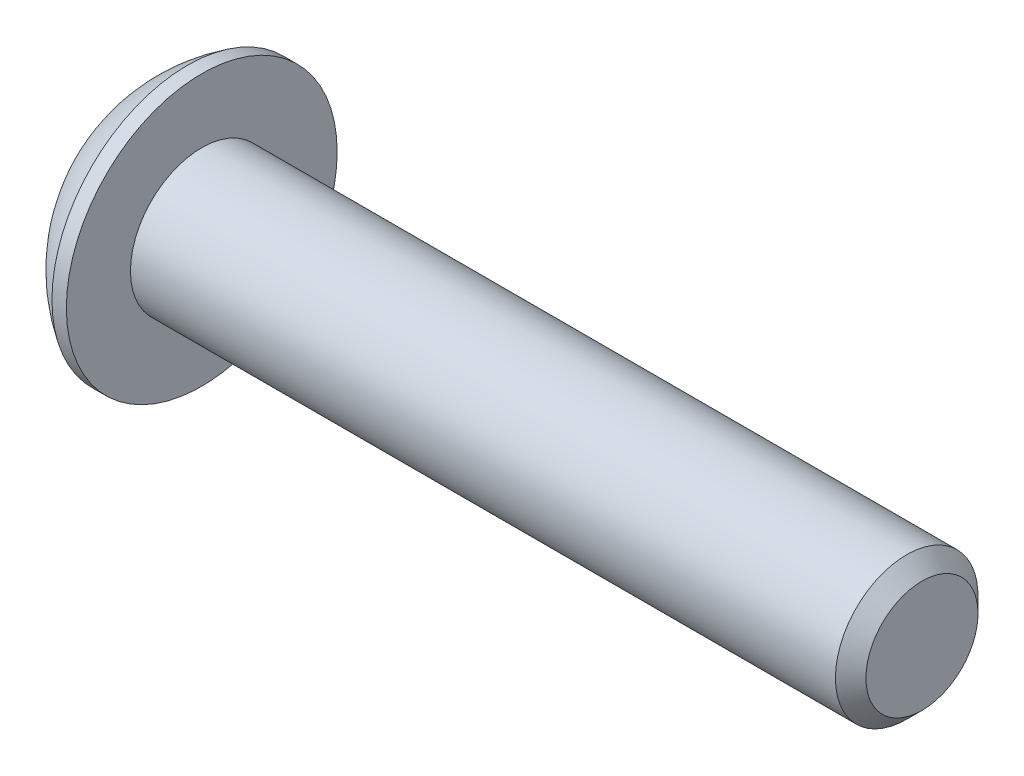
SolidWorks part; units mm, degrees
ref_plane "Plane1" through (0, 0, 0) normal (0, 0, 1) x (1, 0, 0)
ref_plane "Plane2" through (0, 0, 0) normal (0, 1, 0) x (1, 0, 0)
ref_plane "Plane3" through (0, 0, 0) normal (1, 0, 0) x (0, 0, -1)
sketch "BodySke" plane through (0, 0, 0) normal (0, 0, 1) x (1, 0, 0)
  line L0 (14.0208, 0) -> (14.0208, 0.9881)
  line L1 (13.7516, 1.2573) -> (1.3208, 1.2573)
  line L2 (1.3208, 1.2573) -> (1.3208, 2.3876)
  line L3 (1.3208, 2.3876) -> (1.0668, 2.3876)
  line L4 (0, 0) -> (101.6, 0) construction
  line L5 (1.3208, -2.3876) -> (1.0668, -2.3876) construction
  line L6 (55.6768, -1.2573) -> (1.3208, -1.2573) construction
  line L7 (14.0208, 0) -> (0, 0)
  line L8 (0, 1.1938) -> (0, -1.1938) construction
  line L9 (0, 0) -> (0, 1.1938)
  line L10 (14.0208, 0.9881) -> (13.7516, 1.2573)
  line L11 (14.0208, -0.9881) -> (13.7516, -1.2573) construction
  line L12 (1.7755, 9.525) -> (1.7755, -1.2573) construction
  line L13 (1.3208, 9.525) -> (1.3208, -1.2573) construction
  arc A1 (0, 1.1938) -> (1.0668, 2.3876) centre (2.5373, 0) cw
  dimension "D1" = 2.3876
  dimension "Diameter" = 2.5146
  dimension "Length" = 12.7
  dimension "Head_dia" = 4.7752
  dimension "Head_ht" = 1.3208
  dimension "Head_side_ht" = 0.254
  dimension "Minor_dia" = 1.9761
  dimension "Body_ch_ang" = 45
  dimension "Advance" = 0.4547
  dimension "Thread_nom" = 12.7
revolve "BaseBody" add sketch "BodySke" angle 360 about L4
cosmetic thread "ThreadCosmetic" parameters "Thread_length"=12.2453, "Thread_minor"=1.9761
sketch "Sketch2" plane through (0, 0, 0) normal (0, 0, 1) x (1, 0, 0)
  line L0 (0, 0.7874) -> (0.889, 0.7874)
  line L1 (0.889, 0.7874) -> (1.3436, 0)
  line L3 (1.3436, 0) -> (0, 0)
  line L4 (0, 0) -> (0, 0.7874)
  line L5 (0, -0.7874) -> (0.889, -0.7874) construction
  line L6 (0, 0) -> (47.625, 0) construction
  dimension "D2" = 60
  dimension "PreBroach_depth" = 0.889
  dimension "PreBroach_dia" = 1.5748
revolve "PreBroach" cut sketch "Sketch2" angle 360 about L6
sketch "Sketch3" plane through (0, 0, 0) normal (1, 0, 0) x (0, 0, -1)
  line L0 (-0.7874, -0.4546) -> (-0.7874, 0.4546)
  line L1 (-0.7874, 0.4546) -> (0, 0.9092)
  line L2 (0, 0.9092) -> (0.7874, 0.4546)
  line L3 (0.7874, 0.4546) -> (0.7874, -0.4546)
  line L4 (0.7874, -0.4546) -> (0, -0.9092)
  line L5 (0, -0.9092) -> (-0.7874, -0.4546)
  dimension "D1" = 0.7874
  dimension "D2" = 0.7874
  dimension "D3" = 1.5748
  dimension "Hex_size" = 1.5748
extrude "Hex" cut sketch "Sketch3" along normal blind 0.889
sketch "Sketch4" plane through (0, 9.525, 0) normal (1, 0, 0) x (0, 0, -1)
  line L0 (0, -9.525) -> (0.9398, -9.525)
  line L1 (0, -9.525) -> (6.1484, -5.9752) construction
  line L2 (0, -9.525) -> (0.4699, -8.7111)
  line L3 (0.7832, -9.3075) -> (0.8962, -9.2422)
  line L4 (0.58, -8.9555) -> (0.693, -8.8902)
  arc A0 (0.7832, -9.3075) -> (0.58, -8.9555) centre (0, -9.525) ccw
  arc A1 (0.9398, -9.525) -> (0.8962, -9.2422) centre (0, -9.525) ccw
  arc A2 (0.4699, -8.7111) -> (0.693, -8.8902) centre (0, -9.525) cw
  dimension "D1" = 30
  dimension "Spline_n_dim" = 1.6256
  dimension "Spline_m_dim" = 1.8796
  dimension "D2" = 60
  dimension "D3" = 0.2032
  dimension "Spline_p_dim" = 0.4064
extrude "Spline" [suppressed] cut sketch "Sketch4" along normal blind 0.889
pattern_circular "CirPattern1" [suppressed] count 6 every 60 about axis through (0, 0, 0) along (1, 0, 0)
sketch "ThdSchSke" plane through (0, 0, 0) normal (0, 0, 1) x (1, 0, 0)
  line L0 (1.7755, -0.9881) -> (1.5869, -1.2573)
  line L1 (1.7755, -0.9881) -> (1.964, -1.2573)
  line L2 (1.964, -1.2573) -> (1.964, -1.5716)
  line L3 (-3.175, 0) -> (5.1513, 0) construction
  line L5 (1.964, -1.5716) -> (1.5869, -1.5716)
  line L6 (1.5869, -1.5716) -> (1.5869, -1.2573)
  dimension "Thread_minor" = 1.9761
  dimension "Diameter" = 2.5146
  dimension "Start" = 1.7755
  dimension "SideAngle" = 55
  dimension "VeeAngle" = 70
  dimension "Overcut" = 3.1432
revolve "ThreadSchematic" [suppressed] cut sketch "ThdSchSke" angle 360 about L3
pattern_linear "ThdSchPat" [suppressed]
equation "\"D1@BodySke\" = \"Head_dia@BodySke\" * .5"
equation "\"Thread_minor@ThreadCosmetic\" = \"Minor_dia@BodySke\""
equation "\"D1@Sketch3\" = \"Hex_size@Sketch3\" / 2"
equation "\"D2@Sketch3\" = \"D1@Sketch3\""
equation "\"D3@Sketch3\" = \"Hex_size@Sketch3\""
equation "\"D3@Sketch4\" = \"Spline_p_dim@Sketch4\" / 2"
equation "\"D1@Sketch4\" = \"D2@Sketch4\" / 2"
equation "\"Thread_length@ThreadCosmetic\" = ((sgn( (\"Length@BodySke\" - \"Advance@BodySke\" ) - \"Thread_nom@BodySke\" )-1)*( (\"Length@BodySke\" - \"Advance@BodySke\" ) - \"Thread_nom@BodySke\" ))/-2+ \"Thread_nom@BodySke\""
equation "\"Thread_minor@ThdSchSke\" = \"Minor_dia@BodySke\""
equation "\"Diameter@ThdSchSke\" = \"Diameter@BodySke\""
equation "\"Overcut@ThdSchSke\" = \"Diameter@BodySke\" * 1.25"
equation "\"Start@ThdSchSke\" = \"Head_ht@BodySke\" + \"Length@BodySke\" - \"Thread_length@ThreadCosmetic\"  '---Non-countersunk---"
equation "\"Num_threads@ThdSchPat\" = int( \"Thread_length@ThreadCosmetic\" / \"Advance@BodySke\" + 0.999 )  + 1"
equation "\"Advance@ThdSchPat\" = \"Thread_length@ThreadCosmetic\" /  (\"Num_threads@ThdSchPat\" - 1) 'relax it"
equation "\"Num_threads@ThdSchPat\" = \"Num_threads@ThdSchPat\" - sgn( \"Num_threads@ThdSchPat\" - 1) '---chamfered tips only---"
